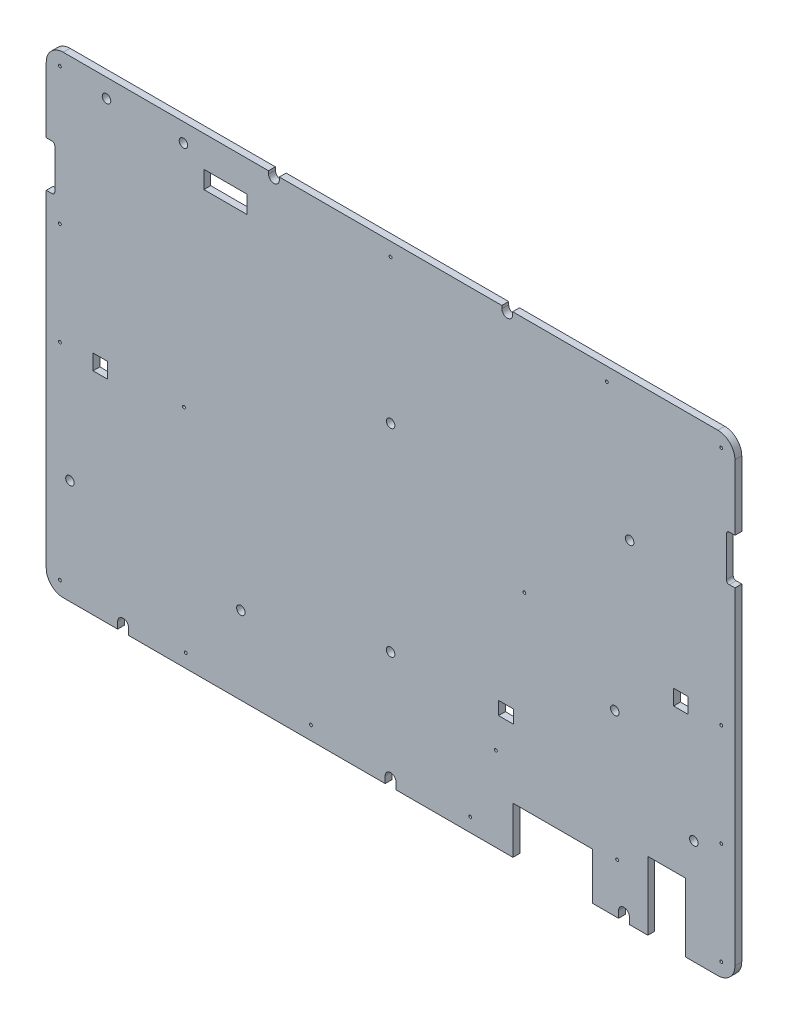
SolidWorks part; units mm, degrees
ref_plane "Ebene vorne" through (0, 0, 0) normal (0, 0, 1) x (1, 0, 0)
ref_plane "Ebene oben" through (0, 0, 0) normal (0, 1, 0) x (1, 0, 0)
ref_plane "Ebene rechts" through (0, 0, 0) normal (1, 0, 0) x (0, 0, -1)
sketch "Skizze1" plane through (0, 0, 0) normal (0, 0, 1) x (1, 0, 0)
  line L0 (60.5, 85.5) -> (-60.5, 85.5)
  line L1 (-60.5, 85.5) -> (-60.5, 2.5)
  line L2 (-60.5, 2.5) -> (60.5, 2.5)
  line L3 (60.5, 2.5) -> (60.5, 85.5)
  point P7 (60.5, 44)
  point P24 (0, 85.5)
  dimension "D1" = 121
  dimension "D2" = 83
  dimension "D3" = 44
extrude "Aufsatz-Linear austragen1" add sketch "Skizze1" along normal blind 1.2
sketch "Skizze2" plane through (0, 0, 0) normal (0, 0, 1) x (1, 0, 0)
  line L0 (35.5, 2.5) -> (35.5, 10.75)
  line L9 (-52.275, 42.355) -> (-49.725, 42.355)
  line L10 (-52.275, 42.355) -> (-52.275, 39.645)
  line L11 (-52.275, 39.645) -> (-49.725, 39.645)
  line L12 (-49.725, 42.355) -> (-49.725, 39.645)
  line L13 (49.725, 42.355) -> (52.275, 42.355)
  line L14 (49.725, 42.355) -> (49.725, 39.645)
  line L15 (49.725, 39.645) -> (52.275, 39.645)
  line L16 (52.275, 42.355) -> (52.275, 39.645)
  line L17 (35.5, 10.75) -> (21.5, 10.75)
  line L18 (21.5, 10.75) -> (21.5, 2.5)
  line L19 (21.5, 2.5) -> (35.5, 2.5)
  line L20 (51.8, 14.5) -> (45.2, 14.5)
  line L21 (45.2, 14.5) -> (45.2, 2.5)
  line L22 (45.2, 2.5) -> (51.8, 2.5)
  line L23 (51.8, 2.5) -> (51.8, 14.5)
  line L25 (-25.2, 80.045) -> (-32.8, 80.045)
  line L26 (-25.2, 80.045) -> (-25.2, 76.955)
  line L27 (-25.2, 76.955) -> (-32.8, 76.955)
  line L28 (-32.8, 80.045) -> (-32.8, 76.955)
  line L29 (21.5613, 25.1196) -> (18.9613, 25.1196)
  line L30 (21.5613, 25.1196) -> (21.5613, 22.8051)
  line L31 (21.5613, 22.8051) -> (18.9613, 22.8051)
  line L32 (18.9613, 25.1196) -> (18.9613, 22.8051)
  circle A0 centre (42, 61) radius 0.75
  circle A1 centre (0, 57.8) radius 0.75
  circle A2 centre (0, 23) radius 0.75
  circle A3 centre (39.4, 33.8) radius 0.75
  circle A6 centre (-26.3, 16.2) radius 0.75
  circle A9 centre (-36.39, 82.2469) radius 0.75
  circle A10 centre (-49.91, 82.2469) radius 0.75
  circle A11 centre (-56.3338, 20.9079) radius 0.75
  circle A12 centre (53.2831, 20.9079) radius 0.75
  point P62 (-51, 39.645)
  point P63 (51, 42.355)
  point P64 (-52.275, 41)
  point P65 (52.275, 41)
  point P66 (-29, 80.045)
  point P67 (-32.8, 78.5)
  point P68 (28.5, 2.5)
  point P69 (48.5, 2.5)
  dimension "D1" = 1.5
  dimension "D7" = 2.71
  dimension "D8" = 2.55
  dimension "D9" = 51
  dimension "D10" = 51
  dimension "D11" = 41
  dimension "D12" = 41
  dimension "D13" = 7.6
  dimension "D14" = 3.09
  dimension "D15" = 29
  dimension "D16" = 78.5
  dimension "D17" = 14
  dimension "D18" = 8.25
  dimension "D19" = 28.5
  dimension "D20" = 48.5
  dimension "D21" = 6.6
  dimension "D22" = 12
  dimension "D23" = 2.5
extrude "Schnitt-Linear austragen1" cut sketch "Skizze2" along normal through all
hole_wizard "Ø0.5 (0.5) Durchmesser Bohrung1" positions "Skizze4" profile "Skizze6" hole size "Ø0.5" standard "DIN" end condition through all
sketch "Skizze4" plane through (0, 0, 0) normal (0, 0, 1) x (1, 0, 0)
  point P0 (58.1, 83.1)
  point P2 (38, 83.1)
  point P4 (0, 83.1)
  point P8 (-58.1, 83.1)
  point P10 (-58.1, 59.1)
  point P12 (-58.1, 41.1)
  point P14 (-36.3, 42.1)
  point P16 (-58.1, 4.9)
  point P18 (-36, 4.9)
  point P20 (-14, 4.9)
  point P22 (14, 4.9)
  point P24 (58.1, 4.9)
  point P26 (39.8, 11.3)
  point P28 (58.1, 40.9)
  point P30 (58.1, 22.9)
  point P32 (23.5, 43.8)
  point P48 (18.5, 17.3)
  dimension "D1" = 14
  dimension "D2" = 14
  dimension "D3" = 36
  dimension "D5" = 58.1
  dimension "D8" = 38
  dimension "D13" = 11.3
  dimension "D14" = 39.8
  dimension "D15" = 18.5
  dimension "D16" = 17.3
  dimension "D17" = 36.3
  dimension "D18" = 42.1
  dimension "D19" = 23.5
  dimension "D20" = 43.8
sketch "Skizze6" plane through (58.1, 83.1, 0) normal (1, 0, 0) x (0, 1, 0)
  line L0 (0, 0) -> (0, 1.2)
  line L1 (0, 1.2) -> (0.25, 1.2)
  line L2 (0.25, 1.2) -> (0.25, 0)
  line L5 (0.25, 0) -> (0, 0)
  line L11 (0, -6.35) -> (0, 107.95) construction
  dimension "Bohrerdurchmesser" = 0.5
  dimension "Bohrungstiefe" = 1.2
fillet "Verrundung1" radius 3 4 edges at (-60.5, 85.5, 0.6) (60.5, 85.5, 0.6) (-60.5, 2.5, 0.6) (60.5, 2.5, 0.6)
sketch "Skizze7" plane through (0, 0, 0) normal (0, 0, 1) x (1, 0, 0)
  line L0 (20.5, 85) -> (20.5, 87.453) construction
  line L1 (19.55, 85) -> (19.55, 87.453)
  line L2 (21.45, 85) -> (21.45, 87.453)
  line L3 (-20.5, 85) -> (-20.5, 88.303) construction
  line L4 (-21.45, 85) -> (-21.45, 88.303)
  line L5 (-19.55, 85) -> (-19.55, 88.303)
  line L6 (41, 3.7) -> (41, -5.6608) construction
  line L7 (41.95, 3.7) -> (41.95, -5.6608)
  line L8 (40.05, 3.7) -> (40.05, -5.6608)
  line L9 (0, 3.7) -> (0, -1.9295) construction
  line L10 (0.95, 3.7) -> (0.95, -1.9295)
  line L11 (-0.95, 3.7) -> (-0.95, -1.9295)
  line L12 (-47, 3.7) -> (-47, -0.8701) construction
  line L13 (-46.05, 3.7) -> (-46.05, -0.8701)
  line L14 (-47.95, 3.7) -> (-47.95, -0.8701)
  arc A0 (19.55, 85) -> (21.45, 85) centre (20.5, 85) ccw
  arc A1 (21.45, 87.453) -> (19.55, 87.453) centre (20.5, 87.453) ccw
  arc A2 (-21.45, 85) -> (-19.55, 85) centre (-20.5, 85) ccw
  arc A3 (-19.55, 88.303) -> (-21.45, 88.303) centre (-20.5, 88.303) ccw
  arc A4 (41.95, 3.7) -> (40.05, 3.7) centre (41, 3.7) ccw
  arc A5 (40.05, -5.6608) -> (41.95, -5.6608) centre (41, -5.6608) ccw
  arc A6 (0.95, 3.7) -> (-0.95, 3.7) centre (0, 3.7) ccw
  arc A7 (-0.95, -1.9295) -> (0.95, -1.9295) centre (0, -1.9295) ccw
  arc A8 (-46.05, 3.7) -> (-47.95, 3.7) centre (-47, 3.7) ccw
  arc A9 (-47.95, -0.8701) -> (-46.05, -0.8701) centre (-47, -0.8701) ccw
  point P2 (20.5, 86.2265)
  point P7 (-20.5, 86.6515)
  point P14 (41, -0.9804)
  point P21 (0, 0.8853)
  point P28 (-47, 1.4149)
  dimension "D1" = 0.95
  dimension "D2" = 41
  dimension "D3" = 47
  dimension "D4" = 20.5
  dimension "D5" = 20.5
  dimension "D6" = 3.7
  dimension "D7" = 85
extrude "Schnitt-Linear austragen2" cut sketch "Skizze7" along normal through all
sketch "Skizze8" plane through (0, 0, 0) normal (0, 0, 1) x (1, 0, 0)
  line L1 (-62.8013, 71) -> (-59, 71)
  line L2 (-62.8013, 71) -> (-62.8013, 63)
  line L3 (-62.8013, 63) -> (-59, 63)
  line L4 (-59, 71) -> (-59, 63)
  line L5 (59, 71) -> (61.6774, 71)
  line L6 (59, 71) -> (59, 63)
  line L7 (59, 63) -> (61.6774, 63)
  line L8 (61.6774, 71) -> (61.6774, 63)
  point P8 (-59, 67)
  point P9 (59, 67)
  point P11 (-62.8013, 67)
  dimension "D1" = 8
  dimension "D2" = 59
  dimension "D3" = 59
  dimension "D4" = 67
extrude "Schnitt-Linear austragen3" cut sketch "Skizze8" along normal through all
fillet "Verrundung2" radius 0.5 4 edges at (59, 71, 0.6) (59, 63, 0.6) (-59, 63, 0.6) (-59, 71, 0.6)
